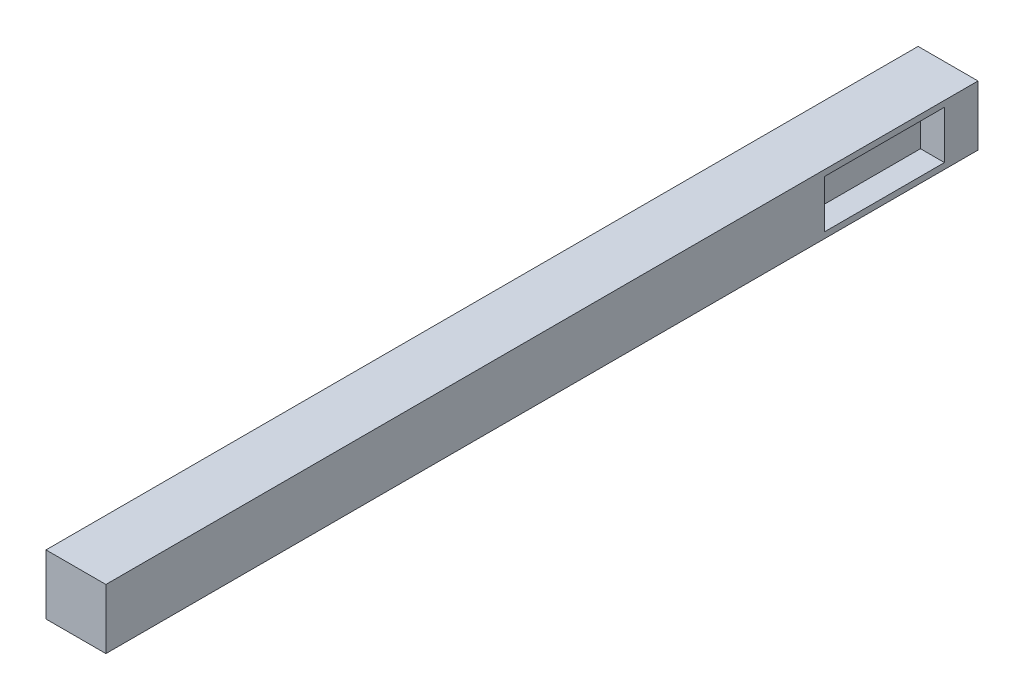
SolidWorks part; units mm, degrees
ref_plane "Front Plane" through (0, 0, 0) normal (0, 0, 1) x (1, 0, 0)
ref_plane "Top Plane" through (0, 0, 0) normal (0, 1, 0) x (1, 0, 0)
ref_plane "Right Plane" through (0, 0, 0) normal (1, 0, 0) x (0, 0, -1)
sketch "Sketch1" plane through (0, 0, 0) normal (0, 0, 1) x (1, 0, 0)
  line L1 (-12.5, 12.5) -> (12.5, 12.5)
  line L2 (-12.5, 12.5) -> (-12.5, -12.5)
  line L3 (-12.5, -12.5) -> (12.5, -12.5)
  line L4 (12.5, 12.5) -> (12.5, -12.5)
  line L5 (-12.5, 12.5) -> (12.5, -12.5) construction
  line L6 (-12.5, -12.5) -> (12.5, 12.5) construction
  point P0 (0, 0)
  dimension "D1" = 25
  dimension "30" = 25
extrude "Boss-Extrude1" add sketch "Sketch1" along normal blind 364
sketch "Sketch2" plane through (12.5, 0, 0) normal (1, 0, 0) x (0, 0, -1)
  line L0 (-364, 12.5) -> (0, 12.5) construction
  line L1 (-64, 10) -> (-14, 10)
  line L2 (-64, 10) -> (-64, -10)
  line L3 (-64, -10) -> (-14, -10)
  line L4 (-14, 10) -> (-14, -10)
  line L6 (-364, -12.5) -> (-364, 12.5) construction
  dimension "D1" = 50
  dimension "D2" = 20
  dimension "D3" = 2.5
  dimension "D4" = 300
extrude "Cut-Extrude1" cut sketch "Sketch2" against normal blind 10
